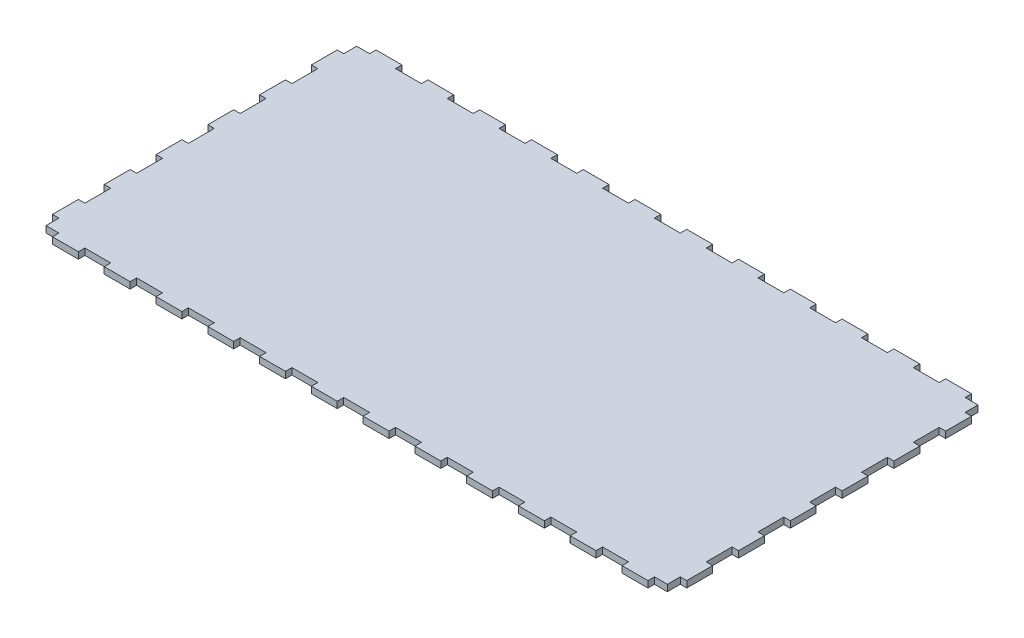
SolidWorks part; units mm, degrees
material "Oak"
ref_plane "Front Plane" through (0, 0, 0) normal (0, 0, 1) x (1, 0, 0)
ref_plane "Top Plane" through (0, 0, 0) normal (0, 1, 0) x (1, 0, 0)
ref_plane "Right Plane" through (0, 0, 0) normal (1, 0, 0) x (0, 0, -1)
sketch "Sketch2" plane through (0, 0, 0) normal (0, 1, 0) x (1, 0, 0)
  line L0 (-292.1, 152.4) -> (-292.1, 158.75)
  line L2 (-304.8, -152.4) -> (-304.8, -139.7)
  line L3 (-304.8, 152.4) -> (-292.1, 152.4)
  line L5 (-304.8, -152.4) -> (304.8, 152.4) construction
  line L6 (-304.8, 152.4) -> (304.8, -152.4) construction
  line L7 (-292.1, 158.75) -> (-266.7, 158.75)
  line L8 (-266.7, 158.75) -> (-266.7, 152.4)
  line L9 (-266.7, 152.4) -> (-241.3, 152.4)
  line L10 (-241.3, 152.4) -> (-241.3, 158.75)
  line L11 (-241.3, 158.75) -> (-215.9, 158.75)
  line L12 (-215.9, 158.75) -> (-215.9, 152.4)
  line L13 (-190.5, 152.4) -> (-190.5, 158.75)
  line L14 (-190.5, 158.75) -> (-165.1, 158.75)
  line L15 (-165.1, 158.75) -> (-165.1, 152.4)
  line L16 (-139.7, 152.4) -> (-139.7, 158.75)
  line L17 (-139.7, 158.75) -> (-114.3, 158.75)
  line L18 (-114.3, 158.75) -> (-114.3, 152.4)
  line L19 (-88.9, 152.4) -> (-88.9, 158.75)
  line L20 (-88.9, 158.75) -> (-63.5, 158.75)
  line L21 (-63.5, 158.75) -> (-63.5, 152.4)
  line L22 (-38.1, 152.4) -> (-38.1, 158.75)
  line L23 (-38.1, 158.75) -> (-12.7, 158.75)
  line L24 (-12.7, 158.75) -> (-12.7, 152.4)
  line L25 (12.7, 152.4) -> (12.7, 158.75)
  line L26 (12.7, 158.75) -> (38.1, 158.75)
  line L27 (38.1, 158.75) -> (38.1, 152.4)
  line L28 (63.5, 152.4) -> (63.5, 158.75)
  line L29 (63.5, 158.75) -> (88.9, 158.75)
  line L30 (88.9, 158.75) -> (88.9, 152.4)
  line L31 (114.3, 152.4) -> (114.3, 158.75)
  line L32 (114.3, 158.75) -> (139.7, 158.75)
  line L33 (139.7, 158.75) -> (139.7, 152.4)
  line L34 (165.1, 152.4) -> (165.1, 158.75)
  line L35 (165.1, 158.75) -> (190.5, 158.75)
  line L36 (190.5, 158.75) -> (190.5, 152.4)
  line L37 (215.9, 152.4) -> (215.9, 158.75)
  line L38 (215.9, 158.75) -> (241.3, 158.75)
  line L39 (241.3, 158.75) -> (241.3, 152.4)
  line L40 (266.7, 152.4) -> (266.7, 158.75)
  line L41 (266.7, 158.75) -> (292.1, 158.75)
  line L42 (292.1, 158.75) -> (292.1, 152.4)
  line L43 (-215.9, 152.4) -> (-190.5, 152.4)
  line L44 (-165.1, 152.4) -> (-139.7, 152.4)
  line L45 (-114.3, 152.4) -> (-88.9, 152.4)
  line L46 (-63.5, 152.4) -> (-38.1, 152.4)
  line L47 (-12.7, 152.4) -> (12.7, 152.4)
  line L48 (38.1, 152.4) -> (63.5, 152.4)
  line L49 (88.9, 152.4) -> (114.3, 152.4)
  line L50 (139.7, 152.4) -> (165.1, 152.4)
  line L51 (190.5, 152.4) -> (215.9, 152.4)
  line L52 (241.3, 152.4) -> (266.7, 152.4)
  line L53 (292.1, 152.4) -> (304.8, 152.4)
  line L54 (-335.28, 0) -> (335.28, 0) construction
  line L55 (292.1, -152.4) -> (304.8, -152.4)
  line L56 (241.3, -152.4) -> (266.7, -152.4)
  line L57 (190.5, -152.4) -> (215.9, -152.4)
  line L58 (139.7, -152.4) -> (165.1, -152.4)
  line L59 (88.9, -152.4) -> (114.3, -152.4)
  line L60 (38.1, -152.4) -> (63.5, -152.4)
  line L61 (-12.7, -152.4) -> (12.7, -152.4)
  line L62 (-63.5, -152.4) -> (-38.1, -152.4)
  line L63 (-114.3, -152.4) -> (-88.9, -152.4)
  line L64 (-165.1, -152.4) -> (-139.7, -152.4)
  line L65 (-215.9, -152.4) -> (-190.5, -152.4)
  line L66 (292.1, -158.75) -> (292.1, -152.4)
  line L67 (266.7, -158.75) -> (292.1, -158.75)
  line L68 (266.7, -152.4) -> (266.7, -158.75)
  line L69 (241.3, -158.75) -> (241.3, -152.4)
  line L70 (215.9, -158.75) -> (241.3, -158.75)
  line L71 (215.9, -152.4) -> (215.9, -158.75)
  line L72 (190.5, -158.75) -> (190.5, -152.4)
  line L73 (165.1, -158.75) -> (190.5, -158.75)
  line L74 (165.1, -152.4) -> (165.1, -158.75)
  line L75 (139.7, -158.75) -> (139.7, -152.4)
  line L76 (114.3, -158.75) -> (139.7, -158.75)
  line L77 (114.3, -152.4) -> (114.3, -158.75)
  line L78 (88.9, -158.75) -> (88.9, -152.4)
  line L79 (63.5, -158.75) -> (88.9, -158.75)
  line L80 (63.5, -152.4) -> (63.5, -158.75)
  line L81 (38.1, -158.75) -> (38.1, -152.4)
  line L82 (12.7, -158.75) -> (38.1, -158.75)
  line L83 (12.7, -152.4) -> (12.7, -158.75)
  line L84 (-12.7, -158.75) -> (-12.7, -152.4)
  line L85 (-38.1, -158.75) -> (-12.7, -158.75)
  line L86 (-38.1, -152.4) -> (-38.1, -158.75)
  line L87 (-63.5, -158.75) -> (-63.5, -152.4)
  line L88 (-88.9, -158.75) -> (-63.5, -158.75)
  line L89 (-88.9, -152.4) -> (-88.9, -158.75)
  line L90 (-114.3, -158.75) -> (-114.3, -152.4)
  line L91 (-139.7, -158.75) -> (-114.3, -158.75)
  line L92 (-139.7, -152.4) -> (-139.7, -158.75)
  line L93 (-165.1, -158.75) -> (-165.1, -152.4)
  line L94 (-190.5, -158.75) -> (-165.1, -158.75)
  line L95 (-190.5, -152.4) -> (-190.5, -158.75)
  line L96 (-215.9, -158.75) -> (-215.9, -152.4)
  line L97 (-241.3, -158.75) -> (-215.9, -158.75)
  line L98 (-241.3, -152.4) -> (-241.3, -158.75)
  line L99 (-266.7, -152.4) -> (-241.3, -152.4)
  line L100 (-266.7, -158.75) -> (-266.7, -152.4)
  line L101 (-292.1, -158.75) -> (-266.7, -158.75)
  line L102 (-304.8, -152.4) -> (-292.1, -152.4)
  line L103 (-292.1, -152.4) -> (-292.1, -158.75)
  line L104 (-304.8, 139.7) -> (-311.15, 139.7)
  line L105 (-311.15, 139.7) -> (-311.15, 114.3)
  line L106 (-311.15, 114.3) -> (-304.8, 114.3)
  line L107 (-304.8, 139.7) -> (-304.8, 152.4)
  line L108 (-304.8, 88.9) -> (-311.15, 88.9)
  line L109 (-311.15, 88.9) -> (-311.15, 63.5)
  line L110 (-311.15, 63.5) -> (-304.8, 63.5)
  line L111 (-304.8, 38.1) -> (-311.15, 38.1)
  line L112 (-311.15, 38.1) -> (-311.15, 12.7)
  line L113 (-311.15, 12.7) -> (-304.8, 12.7)
  line L114 (-304.8, -12.7) -> (-311.15, -12.7)
  line L115 (-311.15, -12.7) -> (-311.15, -38.1)
  line L116 (-311.15, -38.1) -> (-304.8, -38.1)
  line L117 (-304.8, -63.5) -> (-311.15, -63.5)
  line L118 (-311.15, -63.5) -> (-311.15, -88.9)
  line L119 (-311.15, -88.9) -> (-304.8, -88.9)
  line L120 (-304.8, -114.3) -> (-311.15, -114.3)
  line L121 (-311.15, -114.3) -> (-311.15, -139.7)
  line L122 (-311.15, -139.7) -> (-304.8, -139.7)
  line L123 (-304.8, -114.3) -> (-304.8, -88.9)
  line L124 (-304.8, -63.5) -> (-304.8, -38.1)
  line L125 (-304.8, -12.7) -> (-304.8, 12.7)
  line L126 (-304.8, 38.1) -> (-304.8, 63.5)
  line L127 (-304.8, 88.9) -> (-304.8, 114.3)
  line L128 (0, -171.1325) -> (0, 171.1325) construction
  line L129 (304.8, 88.9) -> (304.8, 114.3)
  line L130 (304.8, 38.1) -> (304.8, 63.5)
  line L131 (304.8, -12.7) -> (304.8, 12.7)
  line L132 (304.8, -63.5) -> (304.8, -38.1)
  line L133 (304.8, -114.3) -> (304.8, -88.9)
  line L134 (311.15, -139.7) -> (304.8, -139.7)
  line L135 (311.15, -114.3) -> (311.15, -139.7)
  line L136 (304.8, -114.3) -> (311.15, -114.3)
  line L137 (311.15, -88.9) -> (304.8, -88.9)
  line L138 (311.15, -63.5) -> (311.15, -88.9)
  line L139 (304.8, -63.5) -> (311.15, -63.5)
  line L140 (311.15, -38.1) -> (304.8, -38.1)
  line L141 (311.15, -12.7) -> (311.15, -38.1)
  line L142 (304.8, -12.7) -> (311.15, -12.7)
  line L143 (311.15, 12.7) -> (304.8, 12.7)
  line L144 (311.15, 38.1) -> (311.15, 12.7)
  line L145 (304.8, 38.1) -> (311.15, 38.1)
  line L146 (311.15, 63.5) -> (304.8, 63.5)
  line L147 (311.15, 88.9) -> (311.15, 63.5)
  line L148 (304.8, 88.9) -> (311.15, 88.9)
  line L149 (304.8, 139.7) -> (304.8, 152.4)
  line L150 (311.15, 114.3) -> (304.8, 114.3)
  line L151 (311.15, 139.7) -> (311.15, 114.3)
  line L152 (304.8, 139.7) -> (311.15, 139.7)
  line L153 (304.8, -152.4) -> (304.8, -139.7)
  point P0 (0, 0)
  dimension "D1" = 609.6
  dimension "D2" = 304.8
  dimension "D3" = 12.7
  dimension "D4" = 25.4
  dimension "D5" = 6.35
  dimension "D7" = 25.4
  dimension "D8" = 6.35
  dimension "D9" = 12.7
  dimension "D10" = 25.4
  dimension "D12" = 12.7
  dimension "D6" = 12
  dimension "D11" = 6
extrude "Boss-Extrude1" add sketch "Sketch2" along normal blind 6.35
